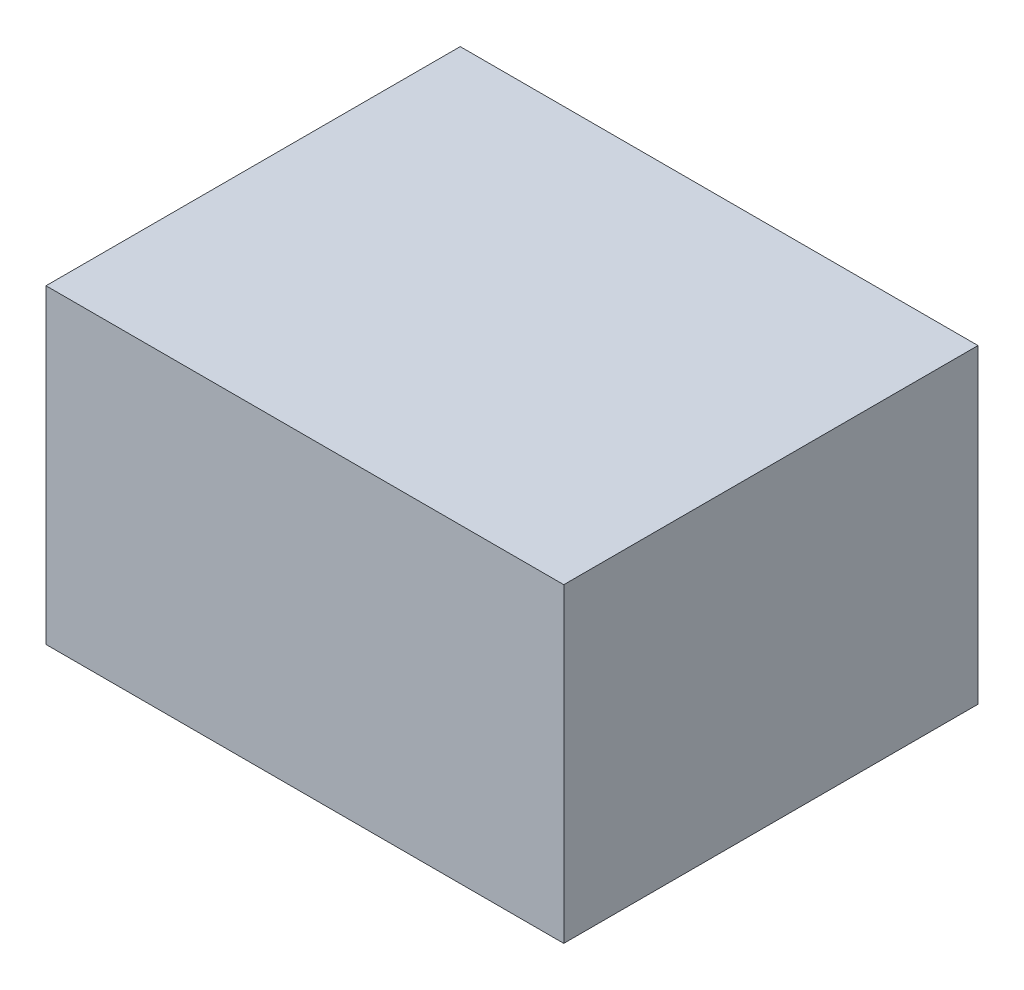
SolidWorks part; units mm, degrees
ref_plane "Přední rovina" through (0, 0, 0) normal (0, 0, 1) x (1, 0, 0)
ref_plane "Horní rovina" through (0, 0, 0) normal (0, 1, 0) x (1, 0, 0)
ref_plane "Pravá rovina" through (0, 0, 0) normal (1, 0, 0) x (0, 0, -1)
sketch "Sketch1" plane through (0, 0, 0) normal (0, 0, 1) x (1, 0, 0)
  line L1 (0, 0) -> (50, 0)
  line L2 (0, 0) -> (0, 30)
  line L3 (0, 30) -> (50, 30)
  line L4 (50, 0) -> (50, 30)
  dimension "D1" = 50
  dimension "D2" = 30
extrude "Boss-Extrude1" add sketch "Sketch1" along normal blind 40
